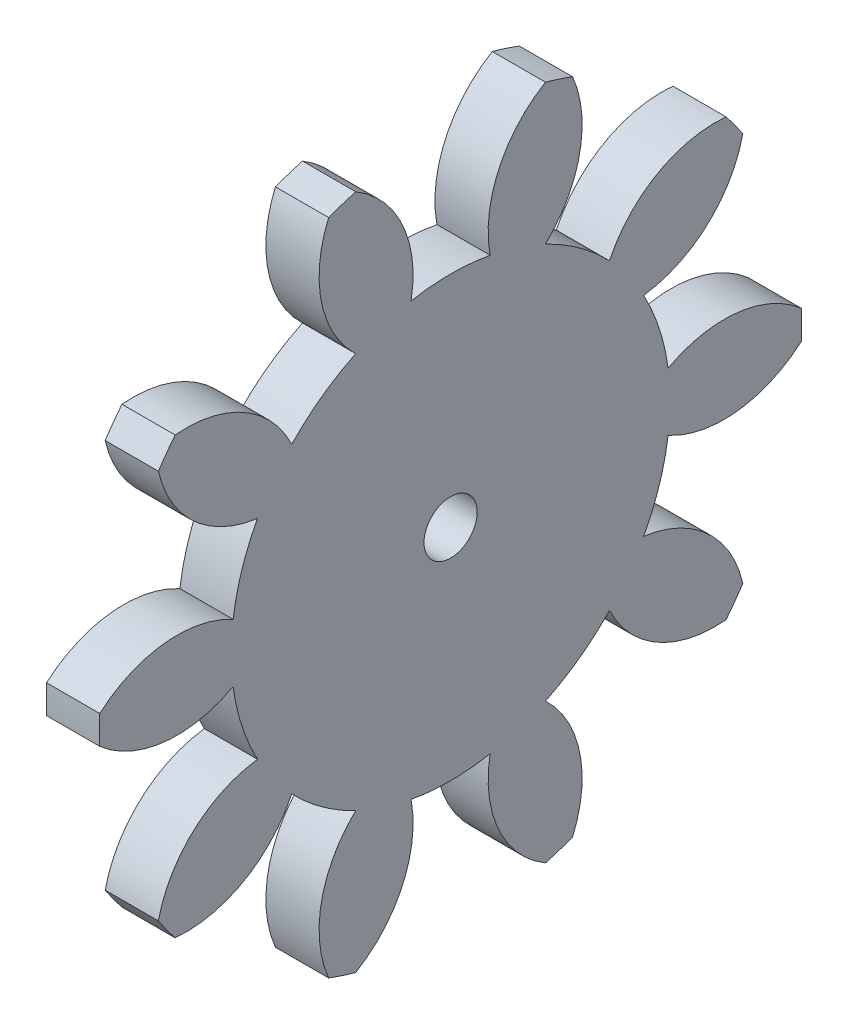
SolidWorks part; units mm, degrees
ref_plane "Plane1" through (0, 0, 0) normal (0, 0, 1) x (1, 0, 0)
ref_plane "Plane2" through (0, 0, 0) normal (0, 1, 0) x (1, 0, 0)
ref_plane "Plane3" through (0, 0, 0) normal (1, 0, 0) x (0, 0, -1)
other "Configuration Table"
sketch "HoldingSke" plane through (0, 0, 0) normal (0, 1, 0) x (1, 0, 0)
  line L0 (0, 0) -> (0.1791, -0.0316)
  line L1 (-15, 0) -> (100, 0) construction
  line L2 (0, 0) -> (-2.1039, 2.3779)
  line L3 (0, 0) -> (-11.863, 4.5341)
  line L4 (0, 0) -> (8.5048, 1.4996)
  line L5 (0, 0) -> (-46.8476, -17.4728)
  line L6 (0, 0) -> (-4.1448, -2.7965)
  line L7 (-2.1039, 2.3779) -> (8.6586, 51.2059)
  line L8 (-76.2, 54.61) -> (-75.3, 54.61)
  line L9 (-67.7845, 28.3722) -> (-49.3413, 33.142)
  line L10 (-76.2, 71.12) -> (104.1128, 71.12)
  line L11 (0, 0) -> (-5, 0)
  line L12 (-76.2, 101.6) -> (-76.013, 101.6)
  line L13 (24.9733, 27.94) -> (52.9518, 28.4284)
  line L14 (24.9733, 27.94) -> (24.9743, 27.94)
  line L15 (24.9733, 27.94) -> (100.4006, 29.5858)
  line L16 (-63.627, -5.5) -> (-12.827, -5.5)
  circle A0 centre (0, 0) radius 2.5
  circle A1 centre (0, 0) radius 20.624
  circle A2 centre (0, 0) radius 37.5
  circle A3 centre (0, 0) radius 2.5
  dimension "MHD" = 41.248
  dimension "Hub_dia" = 75
  dimension "Bore" = 5
  dimension "MBD" = 5
  dimension "Num_teeth" = 10
  dimension "Pitch" = 0.1818
  dimension "Overall_len" = 50
  dimension "Show_teeth" = 10
  dimension "Thickness" = 5
  dimension "OAL" = 50.0001
  dimension "T_dim" = 0.9
  dimension "Ap" = 14.5
  dimension "H" = 19.05
  dimension "Pitch_radius" = 180.3128
  dimension "Width" = 5
  dimension "Backlash" = 0.187
  dimension "Addendum_fac" = 1
  dimension "Dedendum_fac" = 1.25
  dimension "Clearance_fac" = 0.25
  dimension "Dedendum_add" = 0.001
  dimension "Module" = 5.5
sketch "BasProSke" plane through (0, 0, 0) normal (0, 1, 0) x (1, 0, 0)
  line L0 (-10, 0) -> (60, 0) construction
  line L1 (0, 0) -> (0, 33)
  line L2 (0, 0) -> (5, 0)
  line L3 (5, 0) -> (5, 33)
  line L4 (5, 33) -> (0, 33)
  dimension "Thickness" = 5
  dimension "Diameter" = 66
revolve "Base-Revolve" add sketch "BasProSke" angle 360 about L0
sketch "TooCutSke" plane through (0, 0, 0) normal (1, 0, 0) x (0, 0, -1)
  line L1 (0, 0) -> (0, 107) construction
  line L2 (0, 0) -> (-4.6286, 27.1077) construction
  line L3 (0, 0) -> (-16.8175, 51.7589) construction
  line L4 (-4.6286, 27.1077) -> (-8.4087, 25.8794) construction
  arc A0 (3.7156, 20.2865) -> (-3.7156, 20.2865) centre (0, 0) ccw
  arc A1 (8.947, 31.7904) -> (-8.947, 31.7904) centre (0, 0) ccw
  circle A2 centre (0, 0) radius 27.5 construction
  circle A3 centre (0, 0) radius 26.6241 construction
  arc A4 (-3.7156, 20.2865) -> (-8.947, 31.7904) centre (-14.5277, 22.3111) ccw
  arc A5 (8.947, 31.7904) -> (3.7156, 20.2865) centre (14.5277, 22.3111) ccw
  dimension "Root_dia" = 41.248
  dimension "Overcut_dia" = 66.0508
  dimension "Pitch_dia" = 55
  dimension "Base_dia" = 53.2481
  dimension "Flank_rad" = 11
  dimension "Half_ang" = 18
  dimension "Half_CT" = 3.9747
extrude "ToothCut" cut sketch "TooCutSke" along normal through all
fillet "Breaks" [suppressed] radius 0.11
fillet "RootFillets" [suppressed] radius 1.376
pattern_circular "TeethCuts" count 10 every 36 about axis through (-10, 0, 0) along (1, 0, 0) of "ToothCut", "RootFillets", "Breaks"
sketch "HubNeaOneSke" plane through (0, 0, 0) normal (-1, 0, 0) x (0, 0, 1)
  circle A0 centre (0, 0) radius 20.624
  dimension "Diameter" = 41.248
extrude "HubNearOne" [suppressed] add sketch "HubNeaOneSke" along normal blind 45.0001
sketch "HubNeaBotSke" plane through (0, 0, 0) normal (-1, 0, 0) x (0, 0, 1)
  circle A0 centre (0, 0) radius 20.624
  dimension "Diameter" = 41.248
extrude "HubNearBoth" [suppressed] add sketch "HubNeaBotSke" along normal blind 22.5
ref_plane "FarPln" through (5, 0, 0) normal (1, 0, 0) x (0, 0, -1)
sketch "HubFarSke" plane through (5, 0, 0) normal (1, 0, 0) x (0, 0, -1)
  circle A0 centre (0, 0) radius 20.624
  dimension "Diameter" = 41.248
extrude "HubFar" [suppressed] add sketch "HubFarSke" along normal blind 22.5
sketch "BorSke" plane through (0, 0, 0) normal (1, 0, 0) x (0, 0, -1)
  circle A0 centre (0, 0) radius 2.5
  dimension "Diameter" = 5
extrude "Bore" cut sketch "BorSke" along normal mid plane 100.0001
sketch "KeySke" plane through (0, 0, 0) normal (1, 0, 0) x (0, 0, -1)
  line L0 (-1, 0) -> (-1, 3.4)
  line L1 (-1, 3.4) -> (1, 3.4)
  line L2 (1, 3.4) -> (1, 0)
  line L3 (0, 0) -> (0, 34) construction
  line L4 (-1, 0) -> (1, 0)
  dimension "Offset" = 3.4
  dimension "Width" = 2
extrude "Keyway" [suppressed] cut sketch "KeySke" along normal mid plane 100.0001
pattern_circular "Keyway2" [suppressed] count 2 every 90 about axis through (-10, 0, 0) along (1, 0, 0)
equation "' \"Module@HoldingSke\" = 6.35"
equation "' \"Num_teeth@HoldingSke\" = 12"
equation "' \"Ap@HoldingSke\" =  20"
equation "' \"Ap@HoldingSke\" = 20"
equation "' \"Width@HoldingSke\" = 0.5 * 25.4"
equation "' \"Hub_dia@HoldingSke\"= 1 * 25.4"
equation "' \"Hub_dia@HoldingSke\" = 1 * 25.4"
equation "' \"Overall_len@HoldingSke\" = 1.0 * 25.4"
equation "' \"Bore@HoldingSke\" = 0.75 * 25.4"
equation "' \"T_dim@HoldingSke\" = 0.1 * 25.4"
equation "' \"Width@KeySke\" = 0.25 * 25.4"
equation "' \"Show_teeth@HoldingSke\" = 13"
equation "' \"Backlash@HoldingSke\" = 0.009 * 25.4"
equation "' \"Addendum_fac@HoldingSke\" = 1.0"
equation "' \"Dedendum_fac@HoldingSke\" = 1.25"
equation "' \"Dedendum_add@HoldingSke\" = 0.00005 * 25.4"
equation "' \"Clearance_fac@HoldingSke\" = 0.25"
equation "\"Pitch@HoldingSke\" = 1 / \"Module@HoldingSke\""
equation "\"Overcut_dia@TooCutSke\" = (\"Num_teeth@HoldingSke\" + 2 * \"Addendum_fac@HoldingSke\") / \"Pitch@HoldingSke\" + 0.002 * 25.4"
equation "\"Pitch_dia@TooCutSke\" = \"Num_teeth@HoldingSke\" / \"Pitch@HoldingSke\""
equation "\"Base_dia@TooCutSke\" = \"Num_teeth@HoldingSke\" / \"Pitch@HoldingSke\" * cos((\"Ap@HoldingSke\"  * 3.14159265 / 180))"
equation "\"Root_dia@TooCutSke\" = (\"Num_teeth@HoldingSke\" + 2) / \"Pitch@HoldingSke\" - 2 * (\"Addendum_fac@HoldingSke\" + \"Dedendum_fac@HoldingSke\") / \"Pitch@HoldingSke\" - \"Dedendum_add@HoldingSke\" * 2"
equation "\"Half_ang@TooCutSke\" = 180 / \"Num_teeth@HoldingSke\""
equation "\"Half_CT@TooCutSke\" = \"Num_teeth@HoldingSke\" / \"Pitch@HoldingSke\" * sin((3.14159265 / 2 / \"Num_teeth@HoldingSke\")) / 2 - 7 * \"Backlash@HoldingSke\" / 4"
equation "\"Flank_rad@TooCutSke\" = \"Num_teeth@HoldingSke\" / \"Pitch@HoldingSke\" / 5"
equation "\"Radius@RootFillets\" = \"Clearance_fac@HoldingSke\" / \"Pitch@HoldingSke\" + \"Dedendum_add@HoldingSke\""
equation "\"Break_rad@Breaks\" = 0.02 / \"Pitch@HoldingSke\""
equation "\"Thickness@HoldingSke\" = \"Width@HoldingSke\""
equation "\"OAL@HoldingSke\" = \"Thickness@HoldingSke\""
equation "\"MHD@HoldingSke\" = (\"Num_teeth@HoldingSke\" + 2) / \"Pitch@HoldingSke\" - 2 * (\"Addendum_fac@HoldingSke\" + \"Dedendum_fac@HoldingSke\")  / \"Pitch@HoldingSke\" - \"Dedendum_add@HoldingSke\" * 2"
equation "\"MBD@HoldingSke\" = (\"Num_teeth@HoldingSke\" + 2) / \"Pitch@HoldingSke\" - 2 * (\"Addendum_fac@HoldingSke\" + \"Dedendum_fac@HoldingSke\")  / \"Pitch@HoldingSke\" - \"Dedendum_add@HoldingSke\" * 2 - 0.002 * 25.4"
equation "\"MHD@HoldingSke\" = ((sgn( \"MHD@HoldingSke\" - \"Hub_dia@HoldingSke\" )-1)*( \"MHD@HoldingSke\" - \"Hub_dia@HoldingSke\" ))/-2+ \"Hub_dia@HoldingSke\""
equation "\"MBD@HoldingSke\" = ((sgn( \"MBD@HoldingSke\" - \"Bore@HoldingSke\" )-1)*( \"MBD@HoldingSke\" - \"Bore@HoldingSke\" ))/-2+ \"Bore@HoldingSke\""
equation "\"OAL@HoldingSke\" = ((sgn( \"OAL@HoldingSke\" - \"Overall_len@HoldingSke\" )+1)*( \"OAL@HoldingSke\" - \"Overall_len@HoldingSke\" ))/2 + \"Overall_len@HoldingSke\" + 0.000002 * 25.4"
equation "\"Num_teeth@TeethCuts\" = int( \"Show_teeth@HoldingSke\" ) + 1"
equation "\"Num_teeth@TeethCuts\" = ((sgn( \"Num_teeth@TeethCuts\" - \"Num_teeth@HoldingSke\" )-1)*( \"Num_teeth@TeethCuts\" - \"Num_teeth@HoldingSke\" ))/-2+ \"Num_teeth@HoldingSke\""
equation "\"Num_teeth@TeethCuts\" = ((sgn( \"Num_teeth@TeethCuts\" - 2.0)+1)*( \"Num_teeth@TeethCuts\" - 2.0))/2 +2.0"
equation "\"Angle@TeethCuts\" = 360.0 / \"Num_teeth@HoldingSke\""
equation "\"Diameter@BasProSke\" = (\"Num_teeth@HoldingSke\" + 2 * \"Addendum_fac@HoldingSke\") / \"Pitch@HoldingSke\""
equation "\"Thickness@BasProSke\"  = \"Thickness@HoldingSke\""
equation "' \"Fillet_rad@BasProSke\" =  \"Thickness@HoldingSke\" * 0.05"
equation "' \"Fillet_rad@BasProSke\" = \"Thickness@HoldingSke\" * 0.05"
equation "\"MHD@HoldingSke\" = ((sgn( \"MHD@HoldingSke\" - \"Root_dia@TooCutSke\" )-1)*( \"MHD@HoldingSke\" - \"Root_dia@TooCutSke\" ))/-2+ \"Root_dia@TooCutSke\""
equation "\"Diameter@HubNeaOneSke\" = \"MHD@HoldingSke\""
equation "\"Length@HubNearOne\" = \"OAL@HoldingSke\" - \"Thickness@BasProSke\""
equation "\"Diameter@HubNeaBotSke\" = \"MHD@HoldingSke\""
equation "\"Length@HubNearBoth\" = ( \"OAL@HoldingSke\" - \"Thickness@BasProSke\" ) / 2.0"
equation "\"Thickness@FarPln\" = \"Thickness@BasProSke\""
equation "\"Diameter@HubFarSke\" = \"MHD@HoldingSke\""
equation "\"Length@HubFar\" = ( \"OAL@HoldingSke\" - \"Thickness@BasProSke\" ) / 2.0"
equation "\"Diameter@BorSke\" = \"MBD@HoldingSke\""
equation "\"D1@Bore\" = \"OAL@HoldingSke\" * 2.0"
equation "\"D1@Keyway\" = \"OAL@HoldingSke\" * 2.0"
equation "\"Offset@KeySke\" = \"T_dim@HoldingSke\" + \"MBD@HoldingSke\" / 2.0"
